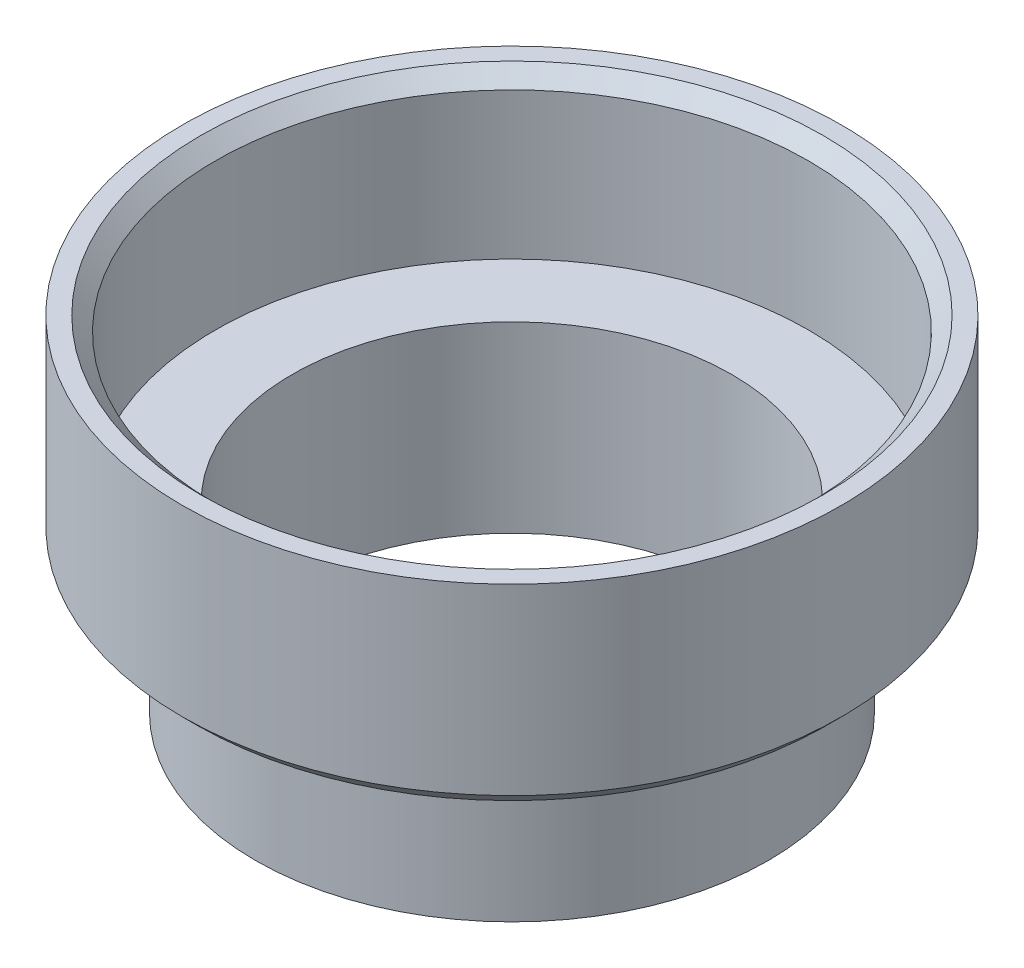
SolidWorks part; units mm, degrees
material "Bronze"
ref_plane "Piano frontale" through (0, 0, 0) normal (0, 0, 1) x (1, 0, 0)
ref_plane "Piano superiore" through (0, 0, 0) normal (0, 1, 0) x (1, 0, 0)
ref_plane "Piano destro" through (0, 0, 0) normal (1, 0, 0) x (0, 0, -1)
sketch "Schizzo1" plane through (0, 0, 0) normal (0, 1, 0) x (1, 0, 0)
  circle A0 centre (0, 0) radius 30
  circle A1 centre (0, 0) radius 35
  dimension "D1" = 60
  dimension "D2" = 70
extrude "Estrusione1" add sketch "Schizzo1" along normal blind 30
sketch "Schizzo2" plane through (0, 30, 0) normal (0, 1, 0) x (1, 0, 0)
  circle A0 centre (0, 0) radius 45
  circle A1 centre (0, 0) radius 30
extrude "Estrusione2" add sketch "Schizzo2" against normal blind 5 from offset 5 offset against normal yes
sketch "Schizzo3" plane through (0, 25, 0) normal (0, 1, 0) x (1, 0, 0)
  circle A0 centre (0, 0) radius 45
  circle A1 centre (0, 0) radius 40.5
extrude "Estrusione3" add sketch "Schizzo3" along normal blind 22
chamfer "Smusso1" distance 2 angle 45 1 edges at (0, 20, 45)
chamfer "Smusso2" distance 2 angle 45 1 edges at (0, 47, 40.5)
sketch "Schizzo4" plane through (0, 25, 0) normal (0, 1, 0) x (1, 0, 0)
  circle A0 centre (0, 0) radius 40.5
extrude "Estrusione4" cut sketch "Schizzo4" along normal blind 20
